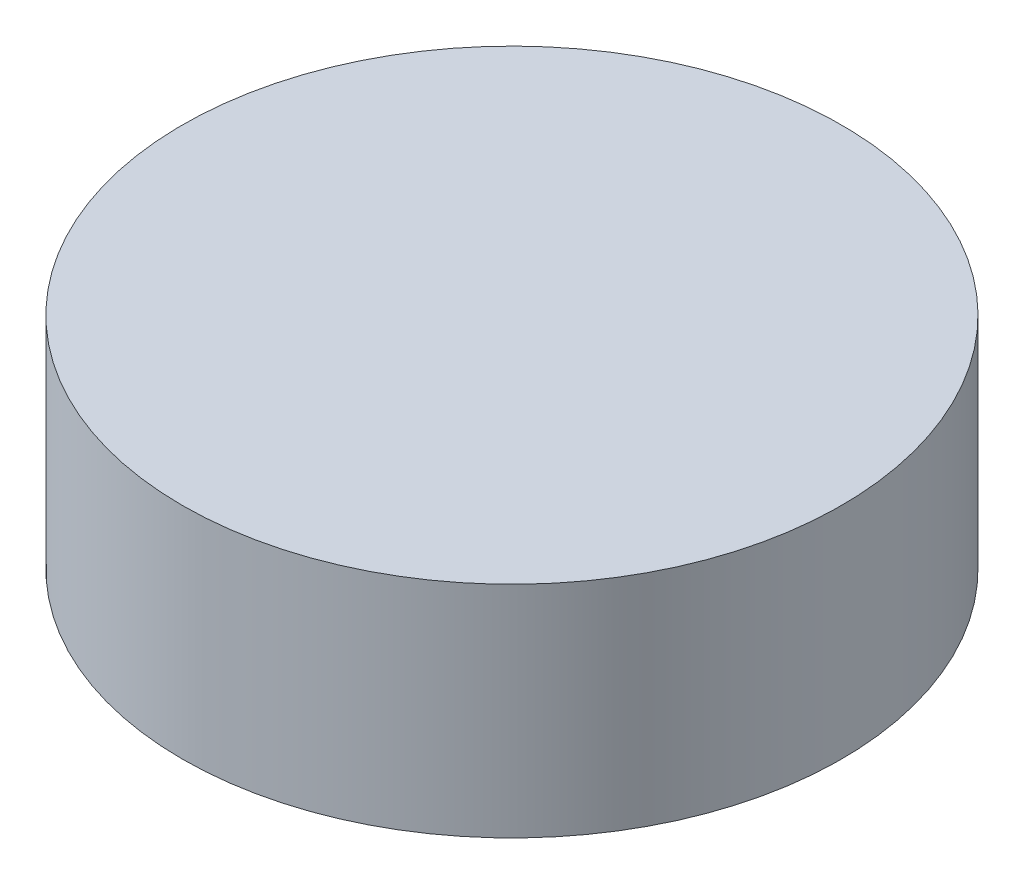
SolidWorks part; units mm, degrees
ref_plane "Front Plane" through (0, 0, 0) normal (0, 0, 1) x (1, 0, 0)
ref_plane "Top Plane" through (0, 0, 0) normal (0, 1, 0) x (1, 0, 0)
ref_plane "Right Plane" through (0, 0, 0) normal (1, 0, 0) x (0, 0, -1)
sketch "Sketch1" plane through (0, 0, 0) normal (0, 1, 0) x (1, 0, 0)
  circle A0 centre (0, 0) radius 45
  dimension "D1" = 90
extrude "Boss-Extrude1" add sketch "Sketch1" along normal blind 30
